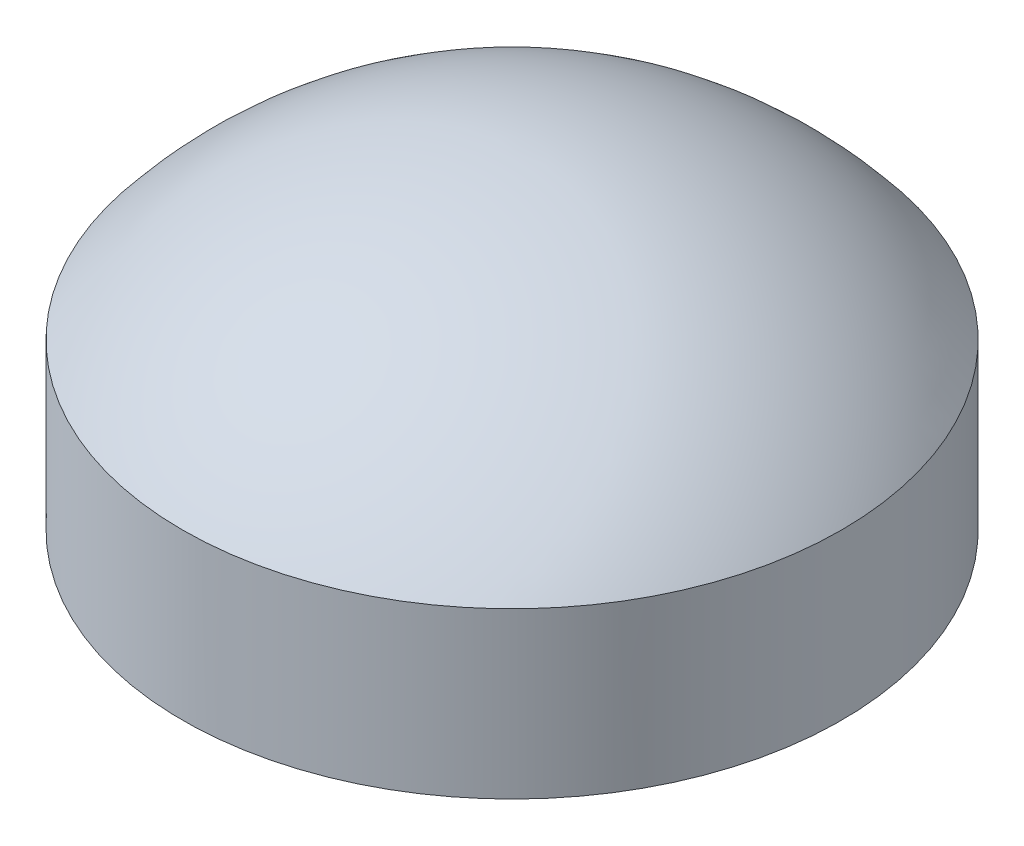
SolidWorks part; units mm, degrees
material "PVC Rigid"
ref_plane "Front Plane" through (0, 0, 0) normal (0, 0, 1) x (1, 0, 0)
ref_plane "Top Plane" through (0, 0, 0) normal (0, 1, 0) x (1, 0, 0)
ref_plane "Right Plane" through (0, 0, 0) normal (1, 0, 0) x (0, 0, -1)
sketch "Sketch1" plane through (0, 0, 0) normal (0, 0, 1) x (1, 0, 0)
  line L0 (44.45, 0) -> (44.45, 25.4)
  line L1 (44.45, 0) -> (50.8, 0)
  line L2 (50.8, 0) -> (50.8, 25.4)
  line L3 (0, -55) -> (0, 55) construction
  line L4 (0, 0) -> (0, 49.9061)
  circle A0 centre (0, -15) radius 60.0663
  circle A1 centre (0, -15) radius 64.9061
  dimension "D1" = 44.45
  dimension "D2" = 25.4
  dimension "D3" = 6.35
  dimension "D4" = 15
revolve "Revolve1" add sketch "Sketch1" angle 360 about L4
